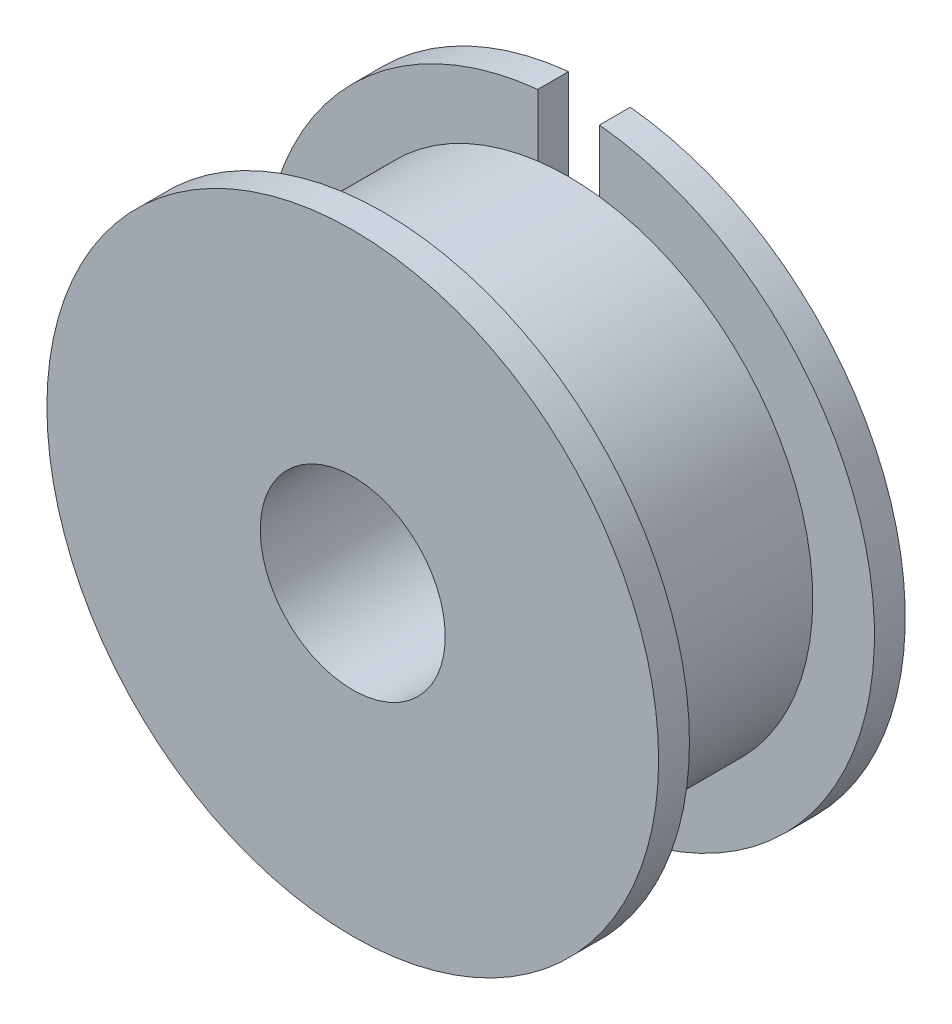
SolidWorks part; units mm, degrees
ref_plane "Front Plane" through (0, 0, 0) normal (0, 0, 1) x (1, 0, 0)
ref_plane "Top Plane" through (0, 0, 0) normal (0, 1, 0) x (1, 0, 0)
ref_plane "Right Plane" through (0, 0, 0) normal (1, 0, 0) x (0, 0, -1)
sketch "Sketch1" plane through (-44.3225, 0, 0) normal (1, 0, 0) x (0, 0, -1)
  line L0 (104.775, -29.06) -> (-10.6045, -29.06) construction
  line L1 (9.525, -13.312) -> (9.525, -44.808) construction
  line L2 (11.1125, -13.312) -> (9.525, -13.312) construction
  line L3 (11.1125, -13.312) -> (11.1125, -44.808) construction
  line L4 (11.1125, -16.487) -> (20.6375, -16.487) construction
  line L5 (20.6375, -13.312) -> (20.6375, -44.808) construction
  line L6 (20.6375, -13.312) -> (22.225, -13.312) construction
  line L7 (22.225, -13.312) -> (22.225, -44.808) construction
  line L8 (22.225, -29.06) -> (9.525, -29.06)
  line L9 (9.525, -13.312) -> (9.525, -24.2975)
  line L10 (11.1125, -13.312) -> (9.525, -13.312)
  line L11 (11.1125, -13.312) -> (11.1125, -16.487)
  line L12 (11.1125, -16.487) -> (20.6375, -16.487)
  line L13 (20.6375, -13.312) -> (20.6375, -16.487)
  line L14 (20.6375, -13.312) -> (22.225, -13.312)
  line L15 (22.225, -13.312) -> (22.225, -24.2975)
  line L16 (104.775, -24.2975) -> (-1.5875, -24.2975) construction
  line L17 (104.775, -24.2975) -> (-1.5875, -24.2975)
revolve "Revolve1" add sketch "Sketch1" angle 360 about L8
sketch "Sketch2" plane through (0, 0, -22.225) normal (0, 0, -1) x (-1, 0, 0)
  line L0 (44.3225, -13.312) -> (44.3225, -44.808) construction
  line L1 (44.3225, -13.312) -> (44.3225, -44.808)
  line L2 (44.3225, -13.312) -> (44.3225, -19.662) construction
  line L3 (45.91, -13.312) -> (45.91, -19.662)
  line L4 (42.735, -13.312) -> (42.735, -19.662)
  arc A0 (45.91, -13.312) -> (42.735, -13.312) centre (44.3225, -13.312) ccw
  arc A1 (42.735, -19.662) -> (45.91, -19.662) centre (44.3225, -19.662) ccw
  point P2 (44.3225, -16.487)
  circle M3 centre (44.3225, -29.06) radius 15.748
  dimension "D1" = 1.5875
  dimension "D2" = 6.35
extrude "Cut-Extrude1" cut sketch "Sketch2" against normal up to surface (1.5875 mm away) contours L4 A1 L1 M3 | L1 A1 L3 M3
